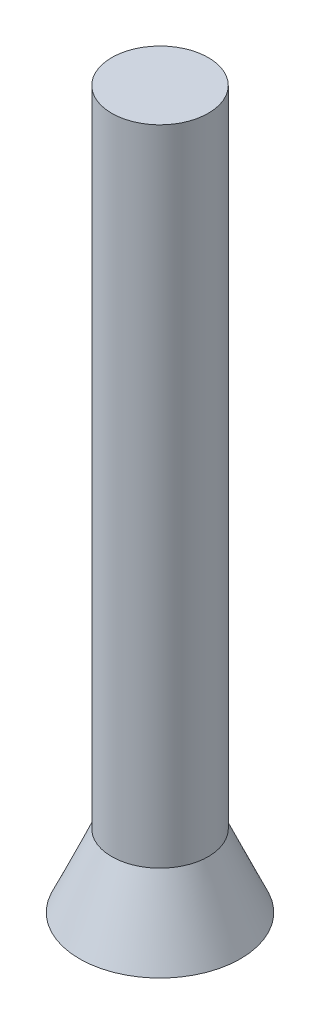
SolidWorks part; units mm, degrees
ref_plane "Front Plane" through (0, 0, 0) normal (0, 0, 1) x (1, 0, 0)
ref_plane "Top Plane" through (0, 0, 0) normal (0, 1, 0) x (1, 0, 0)
ref_plane "Right Plane" through (0, 0, 0) normal (1, 0, 0) x (0, 0, -1)
sketch "Sketch1" plane through (0, 0, 0) normal (0, 1, 0) x (1, 0, 0)
  circle A0 centre (0, 0) radius 2.5
extrude "Boss-Extrude1" add sketch "Sketch1" along normal blind 2.25 draft 24
sketch "Sketch2" plane through (0, 2.25, 0) normal (0, 1, 0) x (1, 0, 0)
  circle A0 centre (0, 0) radius 1.5
extrude "Boss-Extrude2" add sketch "Sketch2" along normal blind 20
sketch "Sketch3" plane through (0, 0, 0) normal (0, -1, 0) x (-1, 0, 0)
  line L0 (0, 0) -> (0, -1.6875) construction
  line L1 (0, 0) -> (-3.4963, 0) construction
  line L2 (-0.5, 0.5) -> (-0.5, 2)
  line L3 (0.5, -2) -> (-0.5, -2)
  line L4 (0.5, -2) -> (0.5, -0.5)
  line L5 (0.5, 2) -> (-0.5, 2)
  line L6 (-0.5, -2) -> (-0.5, -0.5)
  line L7 (0.5, -2) -> (-0.5, 2) construction
  line L8 (0.5, 2) -> (-0.5, -2) construction
  line L9 (2, -0.5) -> (0.5, -0.5)
  line L10 (2, -0.5) -> (2, 0.5)
  line L11 (2, 0.5) -> (0.5, 0.5)
  line L12 (-2, -0.5) -> (-2, 0.5)
  line L13 (2, -0.5) -> (-2, 0.5) construction
  line L14 (2, 0.5) -> (-2, -0.5) construction
  line L15 (0.5, 0.5) -> (0.5, 2)
  line L16 (-0.5, -0.5) -> (-2, -0.5)
  line L17 (-0.5, 0.5) -> (-2, 0.5)
  point P4 (0, 0)
  point P12 (0, 0)
extrude "Cut-Extrude1" cut sketch "Sketch3" against normal blind 1.5 draft 16.5
